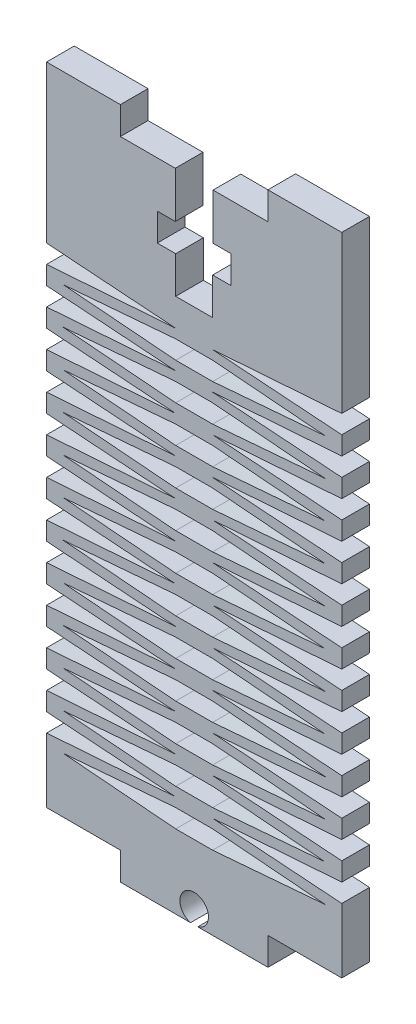
SolidWorks part; units mm, degrees
ref_plane "前视" through (0, 0, 0) normal (0, 0, 1) x (1, 0, 0)
ref_plane "上视" through (0, 0, 0) normal (0, 1, 0) x (1, 0, 0)
ref_plane "右视" through (0, 0, 0) normal (1, 0, 0) x (0, 0, -1)
sketch "草图2" plane through (0, 0, 0) normal (0, 0, 1) x (1, 0, 0)
  line L0 (0, 103.0974) -> (0, -63.3868) construction
  line L1 (2.0479, 48.8553) -> (8, 48.8553)
  line L2 (8, 48.8553) -> (8, 51.8553)
  line L3 (8, 51.8553) -> (16, 51.8553)
  line L4 (16, 51.8553) -> (16, 34.8553)
  line L5 (16, -18.1447) -> (8, -18.1447)
  line L6 (2.0479, 48.8553) -> (2.0479, 43.8553)
  line L7 (2.0479, 43.8553) -> (4, 43.8553)
  line L8 (4, 43.8553) -> (4, 40.8553)
  line L9 (4, 40.8553) -> (2, 40.8553)
  line L10 (2, 40.8553) -> (2, 36.8553)
  line L11 (2, 36.8553) -> (-2, 36.8553)
  line L12 (-8, -21.1447) -> (-0.3905, -21.1447)
  line L13 (8, -21.1447) -> (8, -18.1447)
  line L14 (-8, -21.1447) -> (-8, -18.1447)
  line L15 (0.3905, -21.1447) -> (8, -21.1447)
  line L16 (-2, 40.8553) -> (-2, 36.8553)
  line L17 (-4, 40.8553) -> (-2, 40.8553)
  line L18 (-4, 43.8553) -> (-4, 40.8553)
  line L19 (-2.0479, 43.8553) -> (-4, 43.8553)
  line L20 (-2.0479, 48.8553) -> (-2.0479, 43.8553)
  line L21 (-16, -18.1447) -> (-8, -18.1447)
  line L22 (-16, 51.8553) -> (-16, 34.8553)
  line L23 (-8, 51.8553) -> (-16, 51.8553)
  line L24 (-8, 48.8553) -> (-8, 51.8553)
  line L25 (-2.0479, 48.8553) -> (-8, 48.8553)
  line L26 (-14.2179, -12.1447) -> (-2, -13.1447)
  line L27 (-2, -11.1447) -> (-14.2179, -12.1447)
  line L28 (-2, -10.1447) -> (-16, -11.1447)
  line L29 (-23.902, 34.8553) -> (31.8772, 34.8553) construction
  line L30 (16, 34.8553) -> (2, 33.8553)
  line L31 (2, 33.8553) -> (16, 32.8553)
  line L32 (2, 32.8553) -> (14.2179, 31.8553)
  line L33 (14.2179, 31.8553) -> (2, 30.8553)
  line L34 (-16, -9.1447) -> (-2, -10.1447)
  line L35 (2, 32.8553) -> (-2, 32.8553)
  line L36 (2, 30.8553) -> (-2, 30.8553)
  line L37 (16, 30.8553) -> (2, 29.8553)
  line L38 (2, 29.8553) -> (16, 28.8553)
  line L39 (2, 28.8553) -> (14.2179, 27.8553)
  line L40 (14.2179, 27.8553) -> (2, 26.8553)
  line L41 (2, 28.8553) -> (-2, 28.8553)
  line L42 (2, 26.8553) -> (-2, 26.8553)
  line L43 (16, 26.8553) -> (2, 25.8553)
  line L44 (2, 25.8553) -> (16, 24.8553)
  line L45 (2, 24.8553) -> (14.2179, 23.8553)
  line L46 (14.2179, 23.8553) -> (2, 22.8553)
  line L47 (2, 24.8553) -> (-2, 24.8553)
  line L48 (2, 22.8553) -> (-2, 22.8553)
  line L49 (16, 22.8553) -> (2, 21.8553)
  line L50 (2, 21.8553) -> (16, 20.8553)
  line L51 (2, 20.8553) -> (14.2179, 19.8553)
  line L52 (14.2179, 19.8553) -> (2, 18.8553)
  line L53 (2, 20.8553) -> (-2, 20.8553)
  line L54 (2, 18.8553) -> (-2, 18.8553)
  line L55 (16, 18.8553) -> (2, 17.8553)
  line L56 (2, 17.8553) -> (16, 16.8553)
  line L57 (2, 16.8553) -> (14.2179, 15.8553)
  line L58 (14.2179, 15.8553) -> (2, 14.8553)
  line L59 (2, 16.8553) -> (-2, 16.8553)
  line L60 (2, 14.8553) -> (-2, 14.8553)
  line L61 (16, 14.8553) -> (2, 13.8553)
  line L62 (2, 13.8553) -> (16, 12.8553)
  line L63 (2, 12.8553) -> (14.2179, 11.8553)
  line L64 (14.2179, 11.8553) -> (2, 10.8553)
  line L65 (2, 12.8553) -> (-2, 12.8553)
  line L66 (2, 10.8553) -> (-2, 10.8553)
  line L67 (16, 10.8553) -> (2, 9.8553)
  line L68 (2, 9.8553) -> (16, 8.8553)
  line L69 (2, 8.8553) -> (14.2179, 7.8553)
  line L70 (14.2179, 7.8553) -> (2, 6.8553)
  line L71 (2, 8.8553) -> (-2, 8.8553)
  line L72 (2, 6.8553) -> (-2, 6.8553)
  line L73 (16, 6.8553) -> (2, 5.8553)
  line L74 (2, 5.8553) -> (16, 4.8553)
  line L75 (2, 4.8553) -> (14.2179, 3.8553)
  line L76 (14.2179, 3.8553) -> (2, 2.8553)
  line L77 (2, 4.8553) -> (-2, 4.8553)
  line L78 (2, 2.8553) -> (-2, 2.8553)
  line L79 (16, 2.8553) -> (2, 1.8553)
  line L80 (2, 1.8553) -> (16, 0.8553)
  line L81 (2, 0.8553) -> (14.2179, -0.1447)
  line L82 (14.2179, -0.1447) -> (2, -1.1447)
  line L83 (2, 0.8553) -> (-2, 0.8553)
  line L84 (2, -1.1447) -> (-2, -1.1447)
  line L85 (16, -1.1447) -> (2, -2.1447)
  line L86 (2, -2.1447) -> (16, -3.1447)
  line L87 (2, -3.1447) -> (14.2179, -4.1447)
  line L88 (14.2179, -4.1447) -> (2, -5.1447)
  line L89 (2, -3.1447) -> (-2, -3.1447)
  line L90 (2, -5.1447) -> (-2, -5.1447)
  line L91 (16, -5.1447) -> (2, -6.1447)
  line L92 (2, -6.1447) -> (16, -7.1447)
  line L93 (2, -7.1447) -> (14.2179, -8.1447)
  line L94 (14.2179, -8.1447) -> (2, -9.1447)
  line L95 (2, -7.1447) -> (-2, -7.1447)
  line L96 (2, -9.1447) -> (-2, -9.1447)
  line L97 (16, -9.1447) -> (2, -10.1447)
  line L98 (2, -10.1447) -> (16, -11.1447)
  line L99 (2, -11.1447) -> (14.2179, -12.1447)
  line L100 (14.2179, -12.1447) -> (2, -13.1447)
  line L101 (2, -11.1447) -> (-2, -11.1447)
  line L102 (2, -13.1447) -> (-2, -13.1447)
  line L103 (-14.2179, -8.1447) -> (-2, -9.1447)
  line L104 (-2, -7.1447) -> (-14.2179, -8.1447)
  line L105 (-2, -6.1447) -> (-16, -7.1447)
  line L106 (-16, -5.1447) -> (-2, -6.1447)
  line L107 (-14.2179, -4.1447) -> (-2, -5.1447)
  line L108 (-2, -3.1447) -> (-14.2179, -4.1447)
  line L109 (-2, -2.1447) -> (-16, -3.1447)
  line L110 (-16, -1.1447) -> (-2, -2.1447)
  line L111 (-14.2179, -0.1447) -> (-2, -1.1447)
  line L112 (-2, 0.8553) -> (-14.2179, -0.1447)
  line L113 (-2, 1.8553) -> (-16, 0.8553)
  line L114 (-16, 2.8553) -> (-2, 1.8553)
  line L115 (-14.2179, 3.8553) -> (-2, 2.8553)
  line L116 (-2, 4.8553) -> (-14.2179, 3.8553)
  line L117 (-2, 5.8553) -> (-16, 4.8553)
  line L118 (-16, 6.8553) -> (-2, 5.8553)
  line L119 (-14.2179, 7.8553) -> (-2, 6.8553)
  line L120 (-2, 8.8553) -> (-14.2179, 7.8553)
  line L121 (-2, 9.8553) -> (-16, 8.8553)
  line L122 (-16, 10.8553) -> (-2, 9.8553)
  line L123 (-14.2179, 11.8553) -> (-2, 10.8553)
  line L124 (-2, 12.8553) -> (-14.2179, 11.8553)
  line L125 (-2, 13.8553) -> (-16, 12.8553)
  line L126 (-16, 14.8553) -> (-2, 13.8553)
  line L127 (-14.2179, 15.8553) -> (-2, 14.8553)
  line L128 (-2, 16.8553) -> (-14.2179, 15.8553)
  line L129 (-2, 17.8553) -> (-16, 16.8553)
  line L130 (-16, 18.8553) -> (-2, 17.8553)
  line L131 (-14.2179, 19.8553) -> (-2, 18.8553)
  line L132 (-2, 20.8553) -> (-14.2179, 19.8553)
  line L133 (-2, 21.8553) -> (-16, 20.8553)
  line L134 (-16, 22.8553) -> (-2, 21.8553)
  line L135 (-14.2179, 23.8553) -> (-2, 22.8553)
  line L136 (-2, 24.8553) -> (-14.2179, 23.8553)
  line L137 (-2, 25.8553) -> (-16, 24.8553)
  line L138 (-16, 26.8553) -> (-2, 25.8553)
  line L139 (-14.2179, 27.8553) -> (-2, 26.8553)
  line L140 (-2, 28.8553) -> (-14.2179, 27.8553)
  line L141 (-2, 29.8553) -> (-16, 28.8553)
  line L142 (-16, 30.8553) -> (-2, 29.8553)
  line L143 (-14.2179, 31.8553) -> (-2, 30.8553)
  line L144 (-2, 32.8553) -> (-14.2179, 31.8553)
  line L145 (-2, 33.8553) -> (-16, 32.8553)
  line L146 (-16, 34.8553) -> (-2, 33.8553)
  line L147 (-16, -11.1447) -> (-16, -18.1447)
  line L148 (-16, -7.1447) -> (-16, -9.1447)
  line L149 (-16, -3.1447) -> (-16, -5.1447)
  line L150 (-16, 0.8553) -> (-16, -1.1447)
  line L151 (-16, 4.8553) -> (-16, 2.8553)
  line L152 (-16, 8.8553) -> (-16, 6.8553)
  line L153 (-16, 12.8553) -> (-16, 10.8553)
  line L154 (-16, 16.8553) -> (-16, 14.8553)
  line L155 (-16, 20.8553) -> (-16, 18.8553)
  line L156 (-16, 24.8553) -> (-16, 22.8553)
  line L157 (-16, 28.8553) -> (-16, 26.8553)
  line L158 (-16, 32.8553) -> (-16, 30.8553)
  line L159 (16, 28.8553) -> (16, 26.8553)
  line L160 (16, 32.8553) -> (16, 30.8553)
  line L161 (16, 24.8553) -> (16, 22.8553)
  line L162 (16, 20.8553) -> (16, 18.8553)
  line L163 (16, 16.8553) -> (16, 14.8553)
  line L164 (16, 12.8553) -> (16, 10.8553)
  line L165 (16, 8.8553) -> (16, 6.8553)
  line L166 (16, 4.8553) -> (16, 2.8553)
  line L167 (16, 0.8553) -> (16, -1.1447)
  line L168 (16, -3.1447) -> (16, -5.1447)
  line L169 (16, -7.1447) -> (16, -9.1447)
  line L170 (16, -11.1447) -> (16, -18.1447)
  arc A0 (0.3905, -21.1447) -> (-0.3905, -21.1447) centre (0, -19.6447) ccw
  point P22 (0, 36.8553)
  point P32 (0, -13.1447)
  point P35 (0, -11.1447)
  point P50 (0, -9.1447)
  point P137 (0, -7.1447)
  point P142 (0, -5.1447)
  point P143 (0, -3.1447)
  point P148 (0, -1.1447)
  point P149 (0, 0.8553)
  point P154 (0, 2.8553)
  point P155 (0, 4.8553)
  point P160 (0, 6.8553)
  point P161 (0, 8.8553)
  point P166 (0, 10.8553)
  point P167 (0, 12.8553)
  point P172 (0, 14.8553)
  point P173 (0, 16.8553)
  point P178 (0, 18.8553)
  point P179 (0, 20.8553)
  point P184 (0, 22.8553)
  point P185 (0, 24.8553)
  point P190 (0, 26.8553)
  point P191 (0, 28.8553)
  point P196 (0, 30.8553)
  point P197 (0, 32.8553)
  dimension "D12" = 1.5
  dimension "D11" = 3.1
  dimension "D1" = 8
  dimension "D2" = 8
  dimension "D3" = 3
  dimension "D4" = 12
  dimension "D5" = 5
  dimension "D6" = 3
  dimension "D7" = 2
  dimension "D9" = 70
  dimension "D10" = 3
  dimension "D13" = 1
  dimension "D14" = 2
  dimension "D15" = 1
  dimension "D16" = 0
  dimension "D17" = 1
  dimension "D18" = 1
  dimension "D19" = 12
extrude "凸台-拉伸1" add sketch "草图2" along normal blind 3
